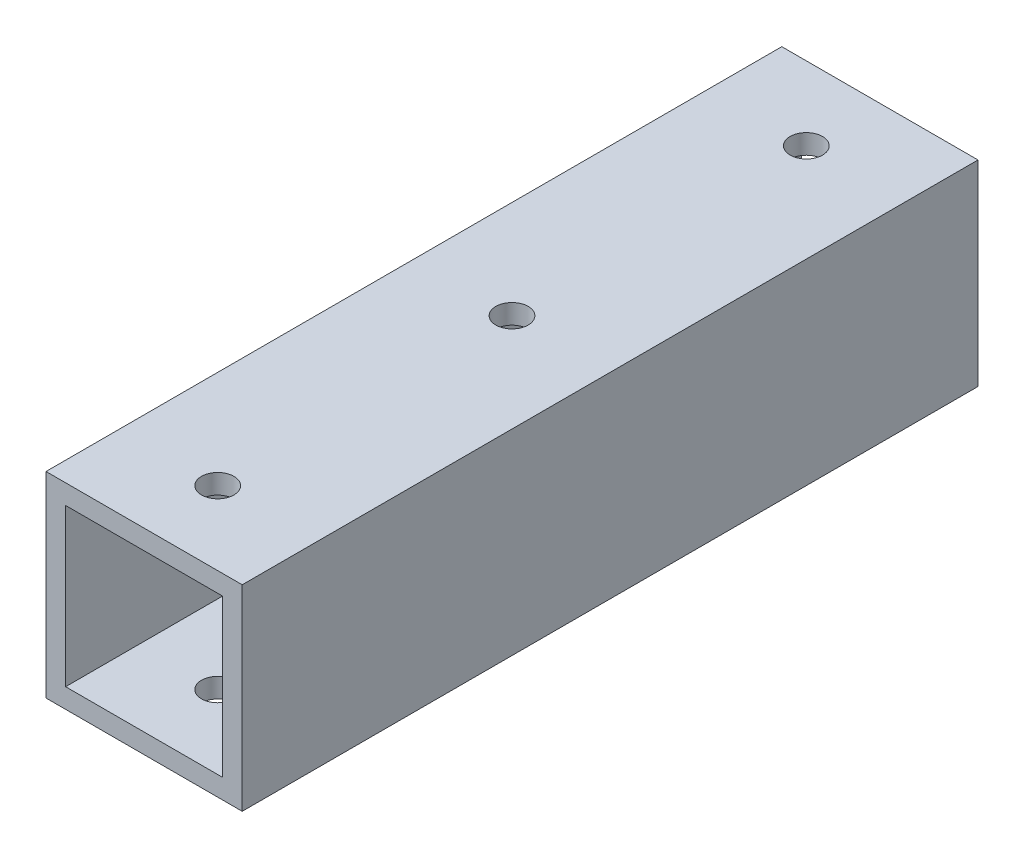
SolidWorks part; units mm, degrees
material "6061 合金"
ref_plane "前视基准面" through (0, 0, 0) normal (0, 0, 1) x (1, 0, 0)
ref_plane "上视基准面" through (0, 0, 0) normal (0, 1, 0) x (1, 0, 0)
ref_plane "右视基准面" through (0, 0, 0) normal (1, 0, 0) x (0, 0, -1)
sketch "草图1" plane through (0, 0, 0) normal (0, 0, 1) x (1, 0, 0)
  line L1 (10, -10) -> (-10, -10)
  line L2 (10, -10) -> (10, 10)
  line L3 (10, 10) -> (-10, 10)
  line L4 (-10, -10) -> (-10, 10)
  line L5 (10, -10) -> (-10, 10) construction
  line L6 (10, 10) -> (-10, -10) construction
  line L7 (8, -8) -> (-8, -8)
  line L8 (8, -8) -> (8, 8)
  line L9 (8, 8) -> (-8, 8)
  line L10 (-8, -8) -> (-8, 8)
  line L11 (8, -8) -> (-8, 8) construction
  line L12 (8, 8) -> (-8, -8) construction
  point P0 (0, 0)
  point P5 (0, 0)
  dimension "D1" = 20
  dimension "D2" = 16
extrude "凸台-拉伸1" add sketch "草图1" along normal blind 75
sketch "草图2" plane through (0, 10, 0) normal (0, 1, 0) x (1, 0, 0)
  line L0 (10, -75) -> (10, 0) construction
  circle A0 centre (0, -37.5) radius 1.65
  circle A1 centre (0, -7.5) radius 1.65
  circle A2 centre (0, -67.5) radius 1.65
  point P9 (10, -37.5)
  dimension "D1" = 3.3
  dimension "D2" = 3.3
  dimension "D3" = 3.3
  dimension "D4" = 30
  dimension "D5" = 30
extrude "切除-拉伸1" cut sketch "草图2" against normal blind 70
